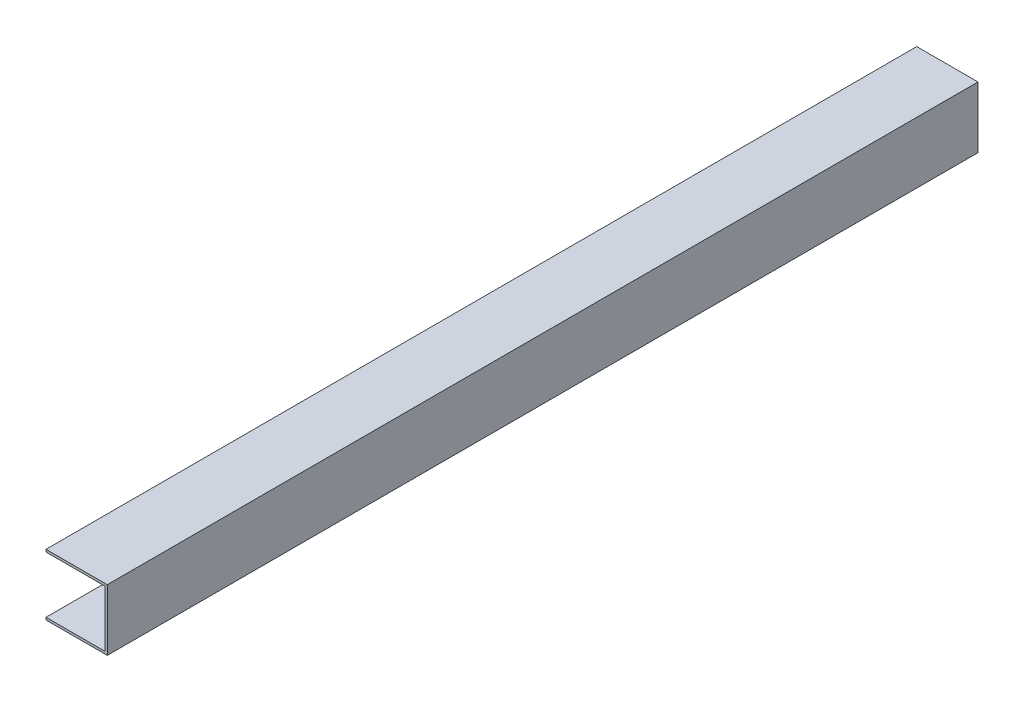
SolidWorks part; units mm, degrees
ref_plane "Alzado" through (0, 0, 0) normal (0, 0, 1) x (1, 0, 0)
ref_plane "Planta" through (0, 0, 0) normal (0, 1, 0) x (1, 0, 0)
ref_plane "Vista lateral" through (0, 0, 0) normal (1, 0, 0) x (0, 0, -1)
sketch "Croquis1" plane through (0, 0, 0) normal (0, 0, 1) x (1, 0, 0)
  line L0 (-1, -1) -> (-24.4, -1)
  line L1 (0, 0) -> (-25.4, 0)
  line L2 (0, 0) -> (0, -25.4)
  line L3 (0, -25.4) -> (-25.4, -25.4)
  line L4 (-25.4, 0) -> (-25.4, -25.4)
  line L5 (-24.4, -1) -> (-24.4, -24.4)
  line L6 (-1, -24.4) -> (-24.4, -24.4)
  line L7 (-1, -1) -> (-1, -24.4)
  dimension "D1" = 25.4
  dimension "D2" = 25.4
  dimension "D3" = 1
extrude "Saliente-Extruir1" add sketch "Croquis1" along normal blind 361
sketch "Croquis2" plane through (-25.4, 0, 0) normal (-1, 0, 0) x (0, 0, 1)
  line L0 (180.5, 0) -> (180.5, -10.6372) construction
  line L5 (361, 0) -> (0, 0) construction
  line L12 (311, -1) -> (311, -24.4)
  line L13 (0, -24.4) -> (0, -1)
  line L14 (0, -1) -> (50, -1)
  line L15 (0, -24.4) -> (50, -24.4)
  line L17 (50, -1) -> (50, -24.4)
  line L18 (361, -24.4) -> (311, -24.4)
  line L19 (361, -1) -> (311, -1)
  line L20 (361, -24.4) -> (361, -1)
extrude "Cortar-Extruir1" cut sketch "Croquis2" against normal up to surface (1 mm away) up to face at (-24.4, -12.7, 180.5)
sketch "Croquis3" plane through (-25.4, 0, 0) normal (-1, 0, 0) x (0, 0, 1)
  line L1 (50, -24.4) -> (61, -24.4)
  line L2 (50, -24.4) -> (50, -1)
  line L3 (50, -1) -> (61, -1)
  line L4 (61, -24.4) -> (61, -1)
  dimension "D1" = 11
extrude "Cortar-Extruir2" cut sketch "Croquis3" against normal up to next
